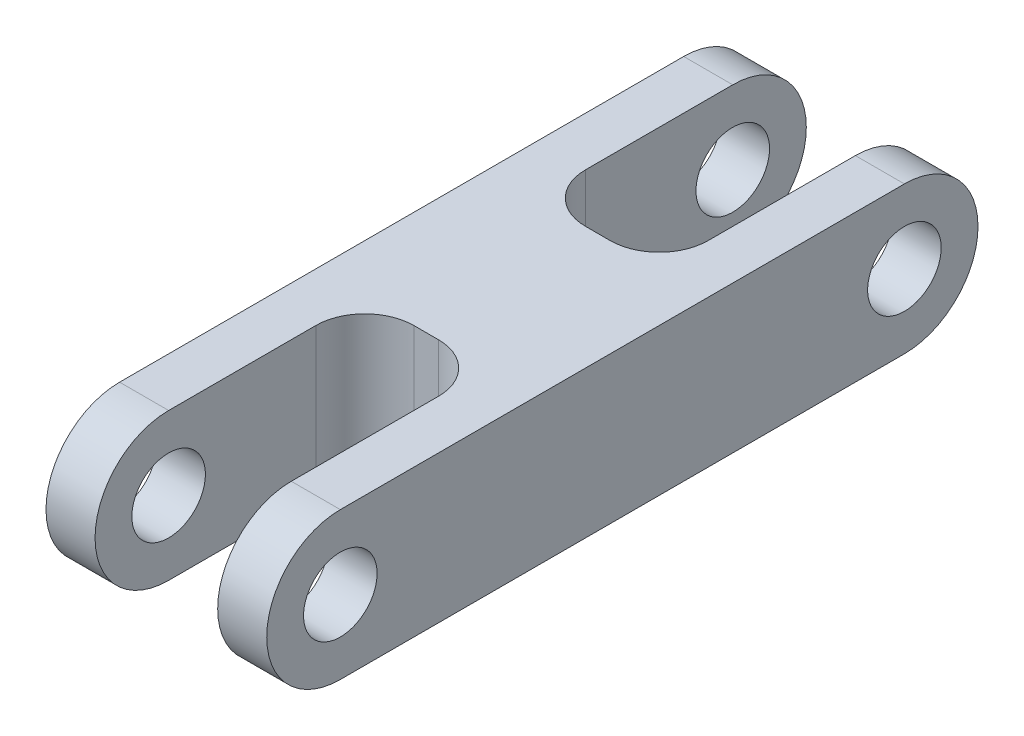
SolidWorks part; units mm, degrees
ref_plane "Front Plane" through (0, 0, 0) normal (0, 0, 1) x (1, 0, 0)
ref_plane "Top Plane" through (0, 0, 0) normal (0, 1, 0) x (1, 0, 0)
ref_plane "Right Plane" through (0, 0, 0) normal (1, 0, 0) x (0, 0, -1)
sketch "Sketch1" plane through (0, 0, 0) normal (1, 0, 0) x (0, 0, -1)
  line L0 (-11.5, 0) -> (11.5, 0) construction
  line L1 (-11.5, 3) -> (11.5, 3)
  line L2 (-11.5, -3) -> (11.5, -3)
  arc A0 (-11.5, 3) -> (-11.5, -3) centre (-11.5, 0) ccw
  arc A1 (11.5, -3) -> (11.5, 3) centre (11.5, 0) ccw
  circle A2 centre (-11.5, 0) radius 1.5
  circle A3 centre (11.5, 0) radius 1.5
  point P2 (0, 0)
  dimension "D3" = 3
  dimension "D1" = 23
  dimension "D2" = 6
extrude "Boss-Extrude1" add sketch "Sketch1" along normal blind 2
sketch "Sketch2" plane through (2, 0, 0) normal (1, 0, 0) x (0, 0, -1)
  line L0 (11.5, 3) -> (-11.5, 3) construction
  line L1 (-3.5, -3) -> (3.5, -3)
  line L2 (-3.5, -3) -> (-3.5, 3)
  line L3 (-3.5, 3) -> (3.5, 3)
  line L4 (3.5, -3) -> (3.5, 3)
  line L5 (-3.5, -3) -> (3.5, 3) construction
  line L6 (-3.5, 3) -> (3.5, -3) construction
  point P0 (0, 0)
  dimension "D1" = 7
extrude "Boss-Extrude2" add sketch "Sketch2" along normal blind 5
sketch "Sketch3" plane through (7, 0, 0) normal (1, 0, 0) x (0, 0, -1)
  line L2 (11.5, 3) -> (-11.5, 3)
  line L3 (-11.5, -3) -> (11.5, -3)
  line L4 (11.5, 3) -> (-11.5, 3)
  line L5 (-11.5, -3) -> (11.5, -3)
  circle A0 centre (11.5, 0) radius 1.5 construction
  circle A1 centre (-11.5, 0) radius 1.5 construction
  arc A2 (-11.5, 3) -> (-11.5, -3) centre (-11.5, 0) ccw
  arc A3 (11.5, -3) -> (11.5, 3) centre (11.5, 0) ccw
  arc A4 (-11.5, 3) -> (-11.5, -3) centre (-11.5, 0) ccw
  arc A5 (11.5, -3) -> (11.5, 3) centre (11.5, 0) ccw
  circle A6 centre (11.5, 0) radius 1.5
  circle A7 centre (-11.5, 0) radius 1.5
  dimension "D1" = 0
extrude "Boss-Extrude3" add sketch "Sketch3" along normal blind 2
fillet "Fillet1" radius 2 4 edges at (7, 0, -3.5) (2, 0, -3.5) (7, 0, 3.5) (2, 0, 3.5)
